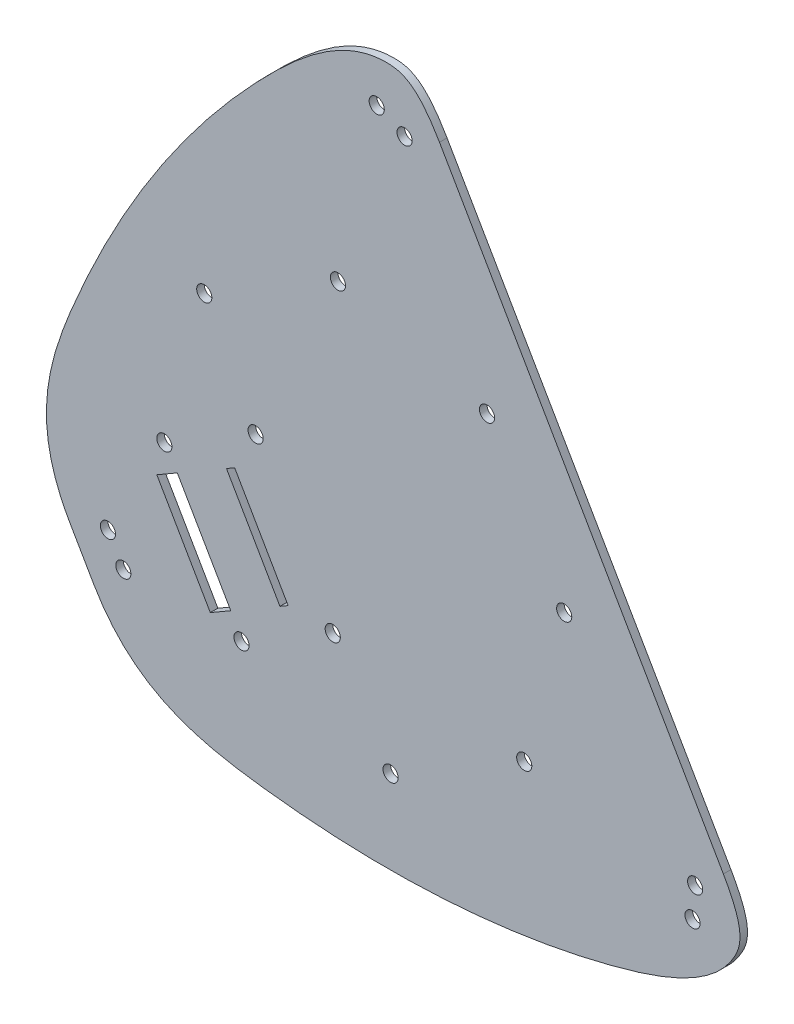
SolidWorks part; units mm, degrees
material "6061 Alloy"
ref_plane "Front Plane" through (0, 0, 0) normal (0, 0, 1) x (1, 0, 0)
ref_plane "Top Plane" through (0, 0, 0) normal (0, 1, 0) x (1, 0, 0)
ref_plane "Right Plane" through (0, 0, 0) normal (1, 0, 0) x (0, 0, -1)
sketch "Sketch3" plane through (0, 0, 0) normal (0, 0, 1) x (1, 0, 0)
  line L4 (-38.7148, 51.9692) -> (-19.8306, 45.8334)
  line L5 (-19.8306, 45.8334) -> (-17.5261, 52.9258)
  line L6 (-17.4337, 61.7728) -> (-27.3336, 64.9895)
  line L21 (-19.8306, 45.8334) -> (-17.5261, 52.9258)
  line L32 (29.7776, -40.0905) -> (25.6493, -59.5126)
  line L34 (42.6158, -56.1663) -> (44.78, -45.9844)
  line L35 (-38.7148, 51.9692) -> (-19.8306, 45.8334)
  line L41 (42.6158, -56.1663) -> (44.78, -45.9844)
  line L43 (-75.5034, -33.777) -> (-76.2534, -32.4779)
  line L44 (29.7776, -40.0905) -> (25.6493, -59.5126)
  line L45 (-88.4519, -43.1496) -> (-81.5946, -55.0267)
  line L49 (-88.4519, -43.1496) -> (-81.5946, -55.0267)
  line L53 (-75.5034, -33.777) -> (-76.2534, -32.4779)
  line L54 (-66.2534, -49.7984) -> (-67.0034, -48.4994)
  line L55 (-66.2534, -49.7984) -> (-67.0034, -48.4994)
  line L65 (-67.0034, -48.4994) -> (-75.5034, -33.777)
  line L66 (-67.0034, -48.4994) -> (-75.5034, -33.777)
  line L120 (-17.4337, 61.7728) -> (-27.3336, 64.9895)
  line L123 (37.072, -41.641) -> (29.7776, -40.0905)
  line L124 (37.072, -41.641) -> (29.7776, -40.0905)
  line L125 (-76.2534, -32.4779) -> (-84.479, -37.2269)
  line L126 (-76.2534, -32.4779) -> (-84.479, -37.2269)
  line L127 (-74.479, -54.5475) -> (-66.2534, -49.7984)
  line L128 (-74.479, -54.5475) -> (-66.2534, -49.7984)
  circle A0 centre (-80.3671, -50.1528) radius 1.4 construction
  circle A1 centre (-80.3671, -50.1528) radius 1.4
  circle A2 centre (-83.6171, -44.5236) radius 1.4 construction
  circle A3 centre (-83.6171, -44.5236) radius 1.4
  circle A4 centre (40.4878, -47.5387) radius 1.4 construction
  circle A5 centre (40.4878, -47.5387) radius 1.4
  circle A6 centre (39.9334, -54.015) radius 1.4 construction
  circle A7 centre (39.9334, -54.015) radius 1.4
  circle A8 centre (-26.8117, 61.5909) radius 1.4 construction
  circle A9 centre (-26.8117, 61.5909) radius 1.4
  circle A10 centre (-20.9258, 58.8328) radius 1.4 construction
  circle A11 centre (-20.9258, 58.8328) radius 1.4
  spline S13 degree 3 poles (24.7179, 1939.55) (-40.9796, -15.9477) (-7.6846, -59.5652) (28.6082, -59.5882) (29.351, -59.5687) (31.5727, -59.4664) (33.0451, -59.3421) (35.2392, -59.0643) (35.9681, -58.9558) (37.4189, -58.6948) (38.141, -58.543) (39.2152, -58.259) (39.5718, -58.1547) (40.2803, -57.9168) (40.6344, -57.7827) (41.3193, -57.4676) (41.6541, -57.287) (42.1009, -56.9453) (42.2428, -56.8172) (46.9231, -51.003) (18.0415, -13.3264) (-1955.3791, -134.035) knots -5.874862 -5.874862 -5.874862 -5.874862 0.125 0.125 0.25 0.25 0.5 0.5 0.625 0.625 0.75 0.75 0.8125 0.8125 0.875 0.875 0.9375 0.9375 0.96875 0.96875 2.170714 2.170714 2.170714 2.170714 only from (25.6493, -59.5126) to (42.6158, -56.1663)
  spline S15 degree 3 poles (-1596.4402, 1095.8307) (-6.1959, -83.8955) (47.3287, -52.1569) (44.6859, -45.3125) (44.6402, -45.2237) (44.5372, -45.0561) (44.4798, -44.9767) (44.295, -44.7482) (44.1545, -44.6077) (43.8618, -44.3491) (43.7084, -44.2297) (43.2343, -43.8915) (42.8999, -43.6922) (42.2097, -43.324) (41.8581, -43.1582) (40.7909, -42.6985) (40.0626, -42.4415) (-19.907, -24.2611) (-152.6968, -222.5725) (503.8128, 1899.6776) knots -2.240385 -2.240385 -2.240385 -2.240385 0.0625 0.0625 0.09375 0.09375 0.125 0.125 0.1875 0.1875 0.25 0.25 0.375 0.375 0.5 0.5 0.75 0.75 20.774541 20.774541 20.774541 20.774541 only from (44.78, -45.9844) to (37.072, -41.641)
  spline S21 degree 3 poles (25.6493, -59.5126) (26.3871, -59.5678) (27.1268, -59.5872) (28.6082, -59.5882) (29.351, -59.5687) (31.5727, -59.4664) (33.0451, -59.3421) (35.2392, -59.0643) (35.9681, -58.9558) (37.4189, -58.6948) (38.141, -58.543) (39.2152, -58.259) (39.5718, -58.1547) (40.2803, -57.9168) (40.6344, -57.7827) (41.3193, -57.4676) (41.6541, -57.287) (42.1009, -56.9453) (42.2428, -56.8172) (42.48, -56.5226) (42.576, -56.3536) (42.6158, -56.1663) knots 0 0 0 0 0.125 0.125 0.25 0.25 0.5 0.5 0.625 0.625 0.75 0.75 0.8125 0.8125 0.875 0.875 0.9375 0.9375 0.96875 0.96875 1 1 1 1
  spline S23 degree 3 poles (44.78, -45.9844) (44.8215, -45.7891) (44.7921, -45.5874) (44.6859, -45.3125) (44.6402, -45.2237) (44.5372, -45.0561) (44.4798, -44.9767) (44.295, -44.7482) (44.1545, -44.6077) (43.8618, -44.3491) (43.7084, -44.2297) (43.2343, -43.8915) (42.8999, -43.6922) (42.2097, -43.324) (41.8581, -43.1582) (40.7909, -42.6985) (40.0626, -42.4415) (38.5836, -41.9931) (37.8327, -41.8027) (37.072, -41.641) knots 0 0 0 0 0.0625 0.0625 0.09375 0.09375 0.125 0.125 0.1875 0.1875 0.25 0.25 0.375 0.375 0.5 0.5 0.75 0.75 1 1 1 1
  spline S28 degree 3 poles (-1081.3823, 1677.9036) (1033.8296, -1050.6308) (-1.3412, 30.1571) (-86.5512, -38.7077) (-87.0137, -39.1451) (-87.6381, -39.885) (-87.8326, -40.144) (-88.1791, -40.6888) (-88.332, -40.9755) (-88.5652, -41.5743) (-88.6482, -41.8927) (-88.6687, -42.3772) (-88.6574, -42.5412) (-86.5848, -52.22) (0.7576, -49.3881) (643.8417, 1816.5113) knots -42.620253 -42.620253 -42.620253 -42.620253 0.25 0.25 0.5 0.5 0.625 0.625 0.75 0.75 0.875 0.875 0.9375 0.9375 4.735946 4.735946 4.735946 4.735946 only from (-84.479, -37.2269) to (-88.4519, -43.1496)
  spline S29 degree 3 poles (1422.702, 1262.6868) (1.3156, 45.9872) (-90.3276, -47.2391) (-81.1687, -55.5106) (-81.0333, -55.6011) (-80.7476, -55.7503) (-80.5948, -55.8101) (-80.2862, -55.9029) (-80.1292, -55.9368) (-79.6524, -56.01) (-79.3265, -56.0209) (-78.6867, -55.9936) (-78.3691, -55.9555) (-77.7373, -55.8431) (-77.4224, -55.7682) (-76.8067, -55.5912) (-76.5045, -55.4888) (4.781, -24.2158) (-267.3218, 885.2553) (901.6563, -1789.9583) knots -4.618862 -4.618862 -4.618862 -4.618862 0.0625 0.0625 0.125 0.125 0.1875 0.1875 0.25 0.25 0.375 0.375 0.5 0.5 0.625 0.625 0.75 0.75 34.787849 34.787849 34.787849 34.787849 only from (-81.5946, -55.0267) to (-74.479, -54.5475)
  spline S32 degree 3 poles (-84.479, -37.2269) (-85.0368, -37.549) (-85.5632, -37.9092) (-86.5512, -38.7077) (-87.0137, -39.1451) (-87.6381, -39.885) (-87.8326, -40.144) (-88.1791, -40.6888) (-88.332, -40.9755) (-88.5652, -41.5743) (-88.6482, -41.8927) (-88.6687, -42.3772) (-88.6574, -42.5412) (-88.5903, -42.8545) (-88.5337, -43.0079) (-88.4519, -43.1496) knots 0 0 0 0 0.25 0.25 0.5 0.5 0.625 0.625 0.75 0.75 0.875 0.875 0.9375 0.9375 1 1 1 1
  spline S33 degree 3 poles (-81.5946, -55.0267) (-81.5127, -55.1685) (-81.41, -55.2927) (-81.1687, -55.5106) (-81.0333, -55.6011) (-80.7476, -55.7503) (-80.5948, -55.8101) (-80.2862, -55.9029) (-80.1292, -55.9368) (-79.6524, -56.01) (-79.3265, -56.0209) (-78.6867, -55.9936) (-78.3691, -55.9555) (-77.7373, -55.8431) (-77.4224, -55.7682) (-76.8067, -55.5912) (-76.5045, -55.4888) (-75.6122, -55.1455) (-75.0364, -54.8693) (-74.479, -54.5475) knots 0 0 0 0 0.0625 0.0625 0.125 0.125 0.1875 0.1875 0.25 0.25 0.375 0.375 0.5 0.5 0.625 0.625 0.75 0.75 1 1 1 1
  spline S88 degree 3 poles (1901.1713, -499.425) (-271.7781, -22.8451) (-31.0312, -5.3941) (-16.7242, 55.9154) (-16.5828, 56.6741) (-16.4473, 57.8266) (-16.4151, 58.2133) (-16.3886, 58.9938) (-16.3938, 59.3868) (-16.4504, 59.9719) (-16.4775, 60.166) (-16.5554, 60.5478) (-16.6059, 60.7361) (-16.7475, 61.1031) (-16.8386, 61.2813) (-17.0235, 61.5097) (-17.0924, 61.5784) (-22.5833, 65.6363) (-73.6411, 16.073) (1045.0765, -1631.5907) knots -19.877801 -19.877801 -19.877801 -19.877801 0.25 0.25 0.5 0.5 0.625 0.625 0.75 0.75 0.8125 0.8125 0.875 0.875 0.9375 0.9375 0.96875 0.96875 3.110081 3.110081 3.110081 3.110081 only from (-17.5261, 52.9258) to (-17.4337, 61.7728)
  spline S89 degree 3 poles (-17.5261, 52.9258) (-17.2858, 53.6656) (-17.0753, 54.4111) (-16.7242, 55.9154) (-16.5828, 56.6741) (-16.4473, 57.8266) (-16.4151, 58.2133) (-16.3886, 58.9938) (-16.3938, 59.3868) (-16.4504, 59.9719) (-16.4775, 60.166) (-16.5554, 60.5478) (-16.6059, 60.7361) (-16.7475, 61.1031) (-16.8386, 61.2813) (-17.0235, 61.5097) (-17.0924, 61.5784) (-17.2504, 61.6951) (-17.3391, 61.7421) (-17.4337, 61.7728) knots 0 0 0 0 0.25 0.25 0.5 0.5 0.625 0.625 0.75 0.75 0.8125 0.8125 0.875 0.875 0.9375 0.9375 0.96875 0.96875 1 1 1 1
  spline S90 degree 3 poles (-221.2274, -1925.5008) (-19.994, 2.4858) (-20.4565, 64.7141) (-27.7048, 65.0425) (-27.8005, 65.0357) (-28.0798, 64.9929) (-28.2599, 64.9351) (-28.7827, 64.7186) (-29.0994, 64.523) (-29.7089, 64.0934) (-30.0008, 63.8559) (-30.5602, 63.3636) (-30.8289, 63.1076) (-31.6131, 62.32) (-32.1075, 61.7694) (-33.0637, 60.6389) (-33.525, 60.0586) (-34.4233, 58.8762) (-34.8599, 58.2742) (-35.7074, 57.0577) (-36.1189, 56.4424) (-36.9164, 55.1968) (-37.3025, 54.5666) (-55.2632, 23.4096) (-35.9596, -28.581) (1634.7279, -1041.6981) knots -1.176486 -1.176486 -1.176486 -1.176486 0.015625 0.015625 0.03125 0.03125 0.0625 0.0625 0.125 0.125 0.1875 0.1875 0.25 0.25 0.375 0.375 0.5 0.5 0.625 0.625 0.75 0.75 0.875 0.875 6.834422 6.834422 6.834422 6.834422 only from (-27.3336, 64.9895) to (-38.7148, 51.9692)
  spline S91 degree 3 poles (-27.3336, 64.9895) (-27.4246, 65.0191) (-27.5173, 65.034) (-27.7048, 65.0425) (-27.8005, 65.0357) (-28.0798, 64.9929) (-28.2599, 64.9351) (-28.7827, 64.7186) (-29.0994, 64.523) (-29.7089, 64.0934) (-30.0008, 63.8559) (-30.5602, 63.3636) (-30.8289, 63.1076) (-31.6131, 62.32) (-32.1075, 61.7694) (-33.0637, 60.6389) (-33.525, 60.0586) (-34.4233, 58.8762) (-34.8599, 58.2742) (-35.7074, 57.0577) (-36.1189, 56.4424) (-36.9164, 55.1968) (-37.3025, 54.5666) (-38.0404, 53.2864) (-38.3932, 52.6369) (-38.7148, 51.9692) knots 0 0 0 0 0.015625 0.015625 0.03125 0.03125 0.0625 0.0625 0.125 0.125 0.1875 0.1875 0.25 0.25 0.375 0.375 0.5 0.5 0.625 0.625 0.75 0.75 0.875 0.875 1 1 1 1
  dimension "D1" = 0
  dimension "D2" = 0
  dimension "D3" = 0
sketch "Sketch1" plane through (0, 0, 0) normal (0, 0, 1) x (1, 0, 0)
  line L20 (-91.7401, -47.1015) -> (-86.6611, -55.8985)
  line L26 (0, 0) -> (-89.2006, -51.5) construction
  line L28 (-17.1887, 67.7718) -> (-9.896, 55.1403) construction
  line L42 (-13.5455, 61.4615) -> (46.4545, -42.4615)
  line L46 (-87.3503, -54.7049) -> (-100.9923, -31.0762) construction
  line L49 (0, 0) -> (16.4545, 9.5) construction
  line L50 (0, 0) -> (21.9393, 0) construction
  circle A0 centre (-80.3671, -50.1528) radius 1.4 construction
  circle A1 centre (-80.3671, -50.1528) radius 1.4 construction
  circle A2 centre (-83.6171, -44.5236) radius 1.4 construction
  circle A3 centre (-83.6171, -44.5236) radius 1.4 construction
  circle A4 centre (39.9334, -54.015) radius 1.4 construction
  circle A5 centre (39.9334, -54.015) radius 1.4 construction
  circle A6 centre (40.4878, -47.5387) radius 1.4 construction
  circle A7 centre (40.4878, -47.5387) radius 1.4 construction
  circle A8 centre (-20.9258, 58.8328) radius 1.4 construction
  circle A9 centre (-20.9258, 58.8328) radius 1.4 construction
  circle A10 centre (-26.8117, 61.5909) radius 1.4 construction
  circle A11 centre (-26.8117, 61.5909) radius 1.4 construction
  circle A12 centre (-26.8117, 61.5909) radius 1.6
  circle A13 centre (-20.9258, 58.8328) radius 1.6
  circle A14 centre (-83.6171, -44.5236) radius 1.6
  circle A15 centre (-80.3671, -50.1528) radius 1.6
  circle A16 centre (40.4878, -47.5387) radius 1.6
  circle A17 centre (39.9334, -54.015) radius 1.6
  spline S0 degree 3 poles (-13.5455, 61.4615) (-18.1035, 69.3562) (-30.3461, 73.3652) (-62.017, 46.6032) (-88.7804, 3.6522) (-100.2664, -32.3335) (-91.7401, -47.1015) knots 0 0 0 0 0.073999 0.286659 0.740795 1 1 1 1
  spline S1 degree 3 poles (46.4545, -42.4615) (51.0125, -50.3562) (48.3631, -62.9631) (9.3511, -77.0099) (-41.2273, -78.7121) (-78.1348, -70.6665) (-86.6611, -55.8985) knots 0 0 0 0 0.073999 0.286659 0.740795 1 1 1 1
  dimension "D1" = 30
  dimension "D5" = 3.2
  dimension "D2" = 103
  dimension "D3" = 19
  dimension "D4" = 120
extrude "Plate" add sketch "Sketch1" along normal blind 1.6
sketch "Sketch5" plane through (0, 0, 0) normal (0, 0, 1) x (1, 0, 0)
  circle A0 centre (-35.0079, 25.2554) radius 1.6
  circle A1 centre (-35.0079, 25.2554) radius 1.4
  circle A2 centre (-35.0079, 25.2554) radius 1.4 construction
  circle A3 centre (-63.2576, 8.9454) radius 1.4
  circle A4 centre (-63.2576, 8.9454) radius 1.4 construction
  circle A5 centre (-55.3903, -50.8127) radius 1.4
  circle A6 centre (-55.3903, -50.8127) radius 1.4 construction
  circle A7 centre (-71.7002, -22.563) radius 1.4
  circle A8 centre (-71.7002, -22.563) radius 1.4 construction
  circle A9 centre (-55.3903, -50.8127) radius 1.6
  circle A11 centre (12.8105, -11.437) radius 1.4
  circle A12 centre (12.8105, -11.437) radius 1.4 construction
  circle A13 centre (4.3679, -42.9454) radius 1.4
  circle A14 centre (4.3679, -42.9454) radius 1.4 construction
  circle A15 centre (-3.4995, 16.8127) radius 1.4
  circle A16 centre (-3.4995, 16.8127) radius 1.4 construction
  circle A17 centre (-23.8818, -59.2554) radius 1.4
  circle A18 centre (-23.8818, -59.2554) radius 1.4 construction
  circle A19 centre (-3.4995, 16.8127) radius 1.6
  circle A20 centre (12.8105, -11.437) radius 1.6
  circle A21 centre (4.3679, -42.9454) radius 1.6
  circle A36 centre (-23.8818, -59.2554) radius 1.6
  circle A37 centre (-71.7002, -22.563) radius 1.6
  circle A38 centre (-63.2576, 8.9454) radius 1.6
  dimension "D5" = 3.2
  dimension "D1" = 0
  dimension "D2" = 0
  dimension "D3" = 0
  dimension "D4" = 0
  dimension "D6" = 0
  dimension "D7" = 0
  dimension "D8" = 0
  dimension "D9" = 0
extrude "Mast" cut sketch "Sketch5" along normal up to next
sketch "Sketch6" plane through (0, 0, 0) normal (0, 0, 1) x (1, 0, 0)
  line L144 (-57.6565, -46.3361) -> (-68.9565, -26.7639)
  line L145 (-68.9565, -26.7639) -> (-73.2866, -29.2639)
  line L146 (-73.2866, -29.2639) -> (-61.9866, -48.8361)
  line L147 (-61.9866, -48.8361) -> (-57.6565, -46.3361)
  line L148 (-57.6565, -46.3361) -> (-68.9565, -26.7639)
  line L149 (-68.9565, -26.7639) -> (-73.2866, -29.2639)
  line L150 (-73.2866, -29.2639) -> (-61.9866, -48.8361)
  line L151 (-61.9866, -48.8361) -> (-57.6565, -46.3361)
  line L152 (-56.8321, -19.7639) -> (-58.5642, -20.7639)
  line L153 (-58.5642, -20.7639) -> (-47.2642, -40.3361)
  line L154 (-47.2642, -40.3361) -> (-45.5321, -39.3361)
  line L155 (-45.5321, -39.3361) -> (-56.8321, -19.7639)
  line L156 (-56.8321, -19.7639) -> (-58.5642, -20.7639)
  line L157 (-58.5642, -20.7639) -> (-47.2642, -40.3361)
  line L158 (-47.2642, -40.3361) -> (-45.5321, -39.3361)
  line L159 (-45.5321, -39.3361) -> (-56.8321, -19.7639)
  dimension "D1" = 0
  dimension "D2" = 0
extrude "Flex slot" cut sketch "Sketch6" along normal up to next
sketch "Sketch8" plane through (0, 0, 0) normal (0, 0, 1) x (1, 0, 0)
  circle A23 centre (-36.1039, -39.6662) radius 1.4
  circle A24 centre (-36.1039, -39.6662) radius 1.4 construction
  circle A25 centre (-52.4039, -11.4338) radius 1.4
  circle A26 centre (-52.4039, -11.4338) radius 1.4 construction
  circle A28 centre (-36.1039, -39.6662) radius 1.6
  circle A29 centre (-52.4039, -11.4338) radius 1.6
  circle A32 centre (12.8105, -11.437) radius 1.6 construction
  dimension "D12" = 0
  dimension "D13" = 0
extrude "Flex screws" cut sketch "Sketch8" along normal up to next
